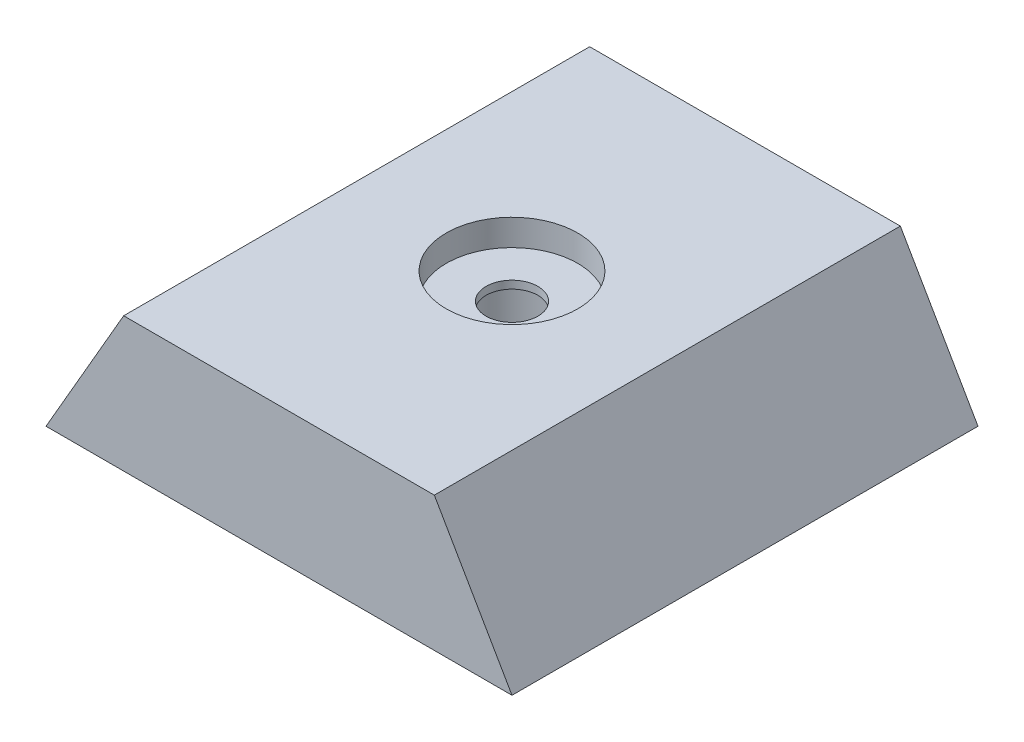
SolidWorks part; units mm, degrees
ref_plane "Plan de face" through (0, 0, 0) normal (0, 0, 1) x (1, 0, 0)
ref_plane "Plan de dessus" through (0, 0, 0) normal (0, 1, 0) x (1, 0, 0)
ref_plane "Plan de droite" through (0, 0, 0) normal (1, 0, 0) x (0, 0, -1)
sketch "Esquisse1" plane through (0, 0, 0) normal (0, 0, 1) x (1, 0, 0)
  line L1 (75, 129.9038) -> (375, 129.9038)
  line L2 (75, 129.9038) -> (0, 0)
  line L3 (0, 0) -> (450, 0)
  line L4 (375, 129.9038) -> (450, 0)
  dimension "D1" = 450
  dimension "D2" = 60
  dimension "D3" = 60
  dimension "D4" = 150
extrude "Boss.-Extru.1" add sketch "Esquisse1" along normal blind 450
sketch "Esquisse2" plane through (0, 0, 0) normal (0, -1, 0) x (1, 0, 0)
  line L0 (0, 450) -> (0, 0) construction
  line L2 (0, 0) -> (450, 0) construction
  circle A0 centre (225, 225) radius 50
  dimension "D3" = 100
  dimension "D1" = 225
  dimension "D2" = 225
sketch "Esquisse3" plane through (0, 129.9038, 0) normal (0, 1, 0) x (1, 0, 0)
  circle A0 centre (225, -225) radius 63.5
  dimension "D1" = 127
extrude "Enlèv. mat.-Extru.1" cut sketch "Esquisse3" against normal blind 25.4
sketch "Esquisse4" plane through (0, 104.5038, 0) normal (0, 1, 0) x (1, 0, 0)
  circle A0 centre (225, -225) radius 25
  dimension "D1" = 50
extrude "Enlèv. mat.-Extru.2" cut sketch "Esquisse4" against normal blind 20
extrude "Enlèv. mat.-Extru.3" cut sketch "Esquisse2" against normal blind 97
shell "Coque1" thickness 30
sketch "Esquisse6" plane through (0, 0, 0) normal (0, -1, 0) x (1, 0, 0)
  circle A0 centre (311.2836, 312.7099) radius 6.9929
equation "\"L\"= 450"
equation "\"H\"= 150"
equation "\"W\"= 450"
equation "\"D1@Esquisse1\"=\"L\""
equation "\"D4@Esquisse1\"=\"H\""
equation "\"D1@Boss.-Extru.1\"=\"W\""
equation "\"R\"= 100"
equation "\"D1@Esquisse2\"=\"W\"/2"
equation "\"D2@Esquisse2\"=\"L\"/2"
equation "\"D3@Esquisse2\"=\"R\""
equation "\"D1@Enlèv. mat.-Extru.3\"=\"H\"-53"
